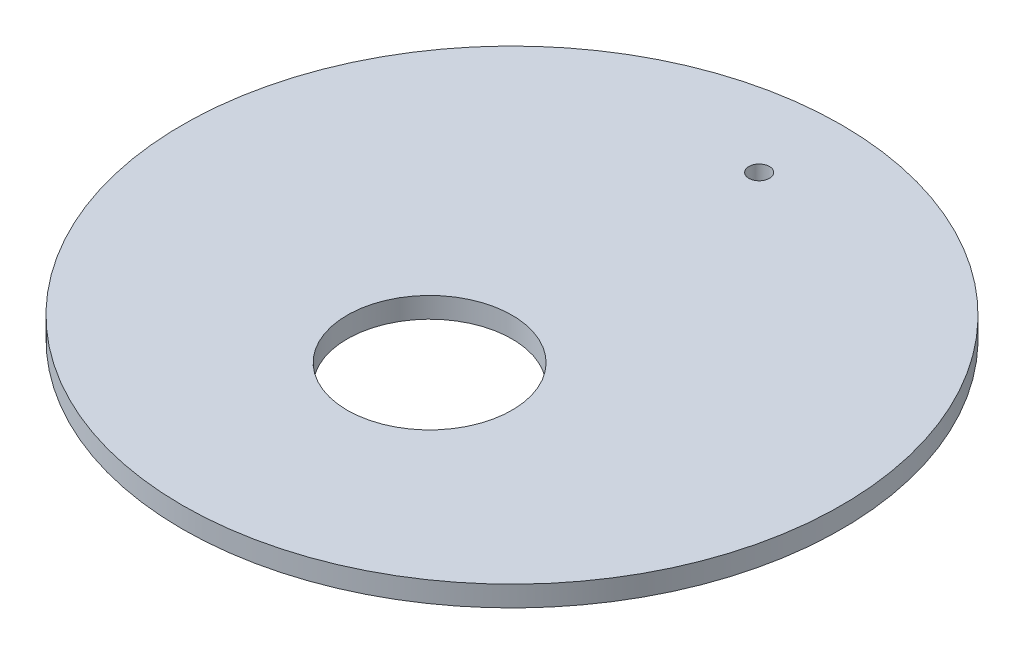
SolidWorks part; units mm, degrees
material "Thornel Mat VMA"
ref_plane "Front Plane" through (0, 0, 0) normal (0, 0, 1) x (1, 0, 0)
ref_plane "Top Plane" through (0, 0, 0) normal (0, 1, 0) x (1, 0, 0)
ref_plane "Right Plane" through (0, 0, 0) normal (1, 0, 0) x (0, 0, -1)
sketch "Sketch1" plane through (0, 0, 0) normal (0, 1, 0) x (1, 0, 0)
  circle A0 centre (0, 0) radius 101.6
extrude "Boss-Extrude1" add sketch "Sketch1" along normal blind 6.35
sketch "Sketch2" plane through (0, 6.35, 0) normal (0, 1, 0) x (1, 0, 0)
  line L0 (0, 0) -> (0, -25.4) construction
  circle A0 centre (0, -25.4) radius 25.4
  circle A1 centre (0, -25.4) radius 76.2
  dimension "D1" = 25.4
extrude "Cut-Extrude1" cut sketch "Sketch2" against normal blind 25.654
sketch "Sketch3" plane through (0, 6.35, 0) normal (0, 1, 0) x (1, 0, 0)
  line L0 (0, -25.4) -> (0, 76.2) construction
  circle A0 centre (0, 76.2) radius 3.175
  dimension "D2" = 6.35
  dimension "D1" = 101.6
extrude "Cut-Extrude2" cut sketch "Sketch3" against normal blind 25.654
